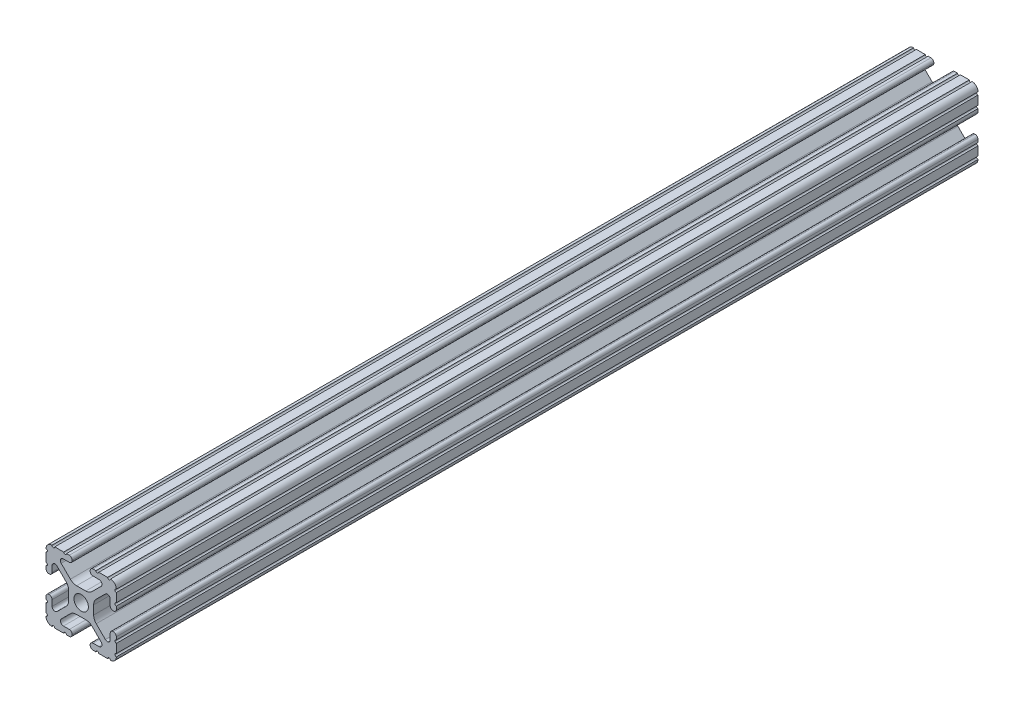
SolidWorks part; units mm, degrees
ref_plane "Front Plane" through (0, 0, 0) normal (0, 0, 1) x (1, 0, 0)
ref_plane "Top Plane" through (0, 0, 0) normal (0, 1, 0) x (1, 0, 0)
ref_plane "Right Plane" through (0, 0, 0) normal (1, 0, 0) x (0, 0, -1)
sketch "Sketch1" plane through (0, 0, 0) normal (0, 0, 1) x (1, 0, 0)
  line L88 (-7.1797, -8.6452) -> (-3.9523, -5.4237)
  line L89 (-1.7093, -4.4958) -> (1.7093, -4.4958)
  line L90 (3.9523, -5.4237) -> (7.1797, -8.6452)
  line L91 (6.4164, -10.4902) -> (4.2875, -10.4902)
  line L92 (3.2385, -11.5392) -> (3.2385, -11.651)
  line L93 (4.2875, -12.7) -> (5.3171, -12.7)
  line L94 (6.3331, -12.7) -> (9.5504, -12.7)
  line L95 (12.7, -9.5504) -> (12.7, -6.3331)
  line L96 (12.7, -5.3171) -> (12.7, -4.2875)
  line L97 (11.651, -3.2385) -> (11.5392, -3.2385)
  line L98 (10.4902, -4.2875) -> (10.4902, -6.4021)
  line L99 (8.7371, -7.1294) -> (5.441, -3.8408)
  line L100 (4.5085, -1.5932) -> (4.5085, 1.5932)
  line L101 (5.441, 3.8408) -> (8.7371, 7.1294)
  line L102 (10.4902, 6.4021) -> (10.4902, 4.2875)
  line L103 (11.5392, 3.2385) -> (11.651, 3.2385)
  line L104 (12.7, 4.2875) -> (12.7, 5.3171)
  line L105 (12.7, 6.3331) -> (12.7, 9.5504)
  line L106 (9.5504, 12.7) -> (6.3331, 12.7)
  line L107 (5.3171, 12.7) -> (4.2875, 12.7)
  line L108 (3.2385, 11.651) -> (3.2385, 11.5392)
  line L109 (4.2875, 10.4902) -> (6.4768, 10.4902)
  line L110 (7.207, 8.7244) -> (3.8983, 5.4232)
  line L111 (1.6558, 4.4958) -> (-1.6558, 4.4958)
  line L112 (-3.8983, 5.4232) -> (-7.207, 8.7244)
  line L113 (-6.4768, 10.4902) -> (-4.2875, 10.4902)
  line L114 (-3.2385, 11.5392) -> (-3.2385, 11.651)
  line L115 (-4.2875, 12.7) -> (-5.3171, 12.7)
  line L116 (-6.3331, 12.7) -> (-9.5504, 12.7)
  line L117 (-12.7, 9.5504) -> (-12.7, 6.3331)
  line L118 (-12.7, 5.3171) -> (-12.7, 4.2875)
  line L119 (-11.651, 3.2385) -> (-11.5392, 3.2385)
  line L120 (-10.4902, 4.2875) -> (-10.4902, 6.4021)
  line L121 (-8.7371, 7.1294) -> (-5.441, 3.8408)
  line L122 (-4.5085, 1.5932) -> (-4.5085, -1.5932)
  line L123 (-5.441, -3.8408) -> (-8.7371, -7.1294)
  line L124 (-10.4902, -6.4021) -> (-10.4902, -4.2875)
  line L125 (-11.5392, -3.2385) -> (-11.651, -3.2385)
  line L126 (-12.7, -4.2875) -> (-12.7, -5.3171)
  line L127 (-12.7, -6.3331) -> (-12.7, -9.5504)
  line L128 (-9.5504, -12.7) -> (-6.3331, -12.7)
  line L129 (-5.3171, -12.7) -> (-4.2875, -12.7)
  line L130 (-3.2385, -11.651) -> (-3.2385, -11.5392)
  line L131 (-4.2875, -10.4902) -> (-6.4164, -10.4902)
  circle A1 centre (0, 0) radius 2.6035
  arc A104 (-7.1797, -8.6452) -> (-6.4164, -10.4902) centre (-6.4164, -9.4098) ccw
  arc A105 (-1.7093, -4.4958) -> (-3.9523, -5.4237) centre (-1.7093, -7.6708) ccw
  arc A106 (3.9523, -5.4237) -> (1.7093, -4.4958) centre (1.7093, -7.6708) ccw
  arc A107 (6.4164, -10.4902) -> (7.1797, -8.6452) centre (6.4164, -9.4098) ccw
  arc A108 (4.2875, -10.4902) -> (3.2385, -11.5392) centre (4.2875, -11.5392) ccw
  arc A109 (3.2385, -11.651) -> (4.2875, -12.7) centre (4.2875, -11.651) ccw
  arc A110 (6.3331, -12.7) -> (5.3171, -12.7) centre (5.8251, -12.7) ccw
  arc A111 (10.5664, -12.6998) -> (9.5504, -12.7) centre (10.0584, -12.7) ccw
  arc A112 (10.5664, -12.6998) -> (12.6998, -10.5664) centre (10.5918, -10.5918) ccw
  arc A113 (12.7, -9.5504) -> (12.6998, -10.5664) centre (12.7, -10.0584) ccw
  arc A114 (12.7, -5.3171) -> (12.7, -6.3331) centre (12.7, -5.8251) ccw
  arc A115 (12.7, -4.2875) -> (11.651, -3.2385) centre (11.651, -4.2875) ccw
  arc A116 (11.5392, -3.2385) -> (10.4902, -4.2875) centre (11.5392, -4.2875) ccw
  arc A117 (8.7371, -7.1294) -> (10.4902, -6.4021) centre (9.4628, -6.4021) ccw
  arc A118 (4.5085, -1.5932) -> (5.441, -3.8408) centre (7.6835, -1.5932) ccw
  arc A119 (5.441, 3.8408) -> (4.5085, 1.5932) centre (7.6835, 1.5932) ccw
  arc A120 (10.4902, 6.4021) -> (8.7371, 7.1294) centre (9.4628, 6.4021) ccw
  arc A121 (10.4902, 4.2875) -> (11.5392, 3.2385) centre (11.5392, 4.2875) ccw
  arc A122 (11.651, 3.2385) -> (12.7, 4.2875) centre (11.651, 4.2875) ccw
  arc A123 (12.7, 6.3331) -> (12.7, 5.3171) centre (12.7, 5.8251) ccw
  arc A124 (12.6998, 10.5664) -> (12.7, 9.5504) centre (12.7, 10.0584) ccw
  arc A125 (12.6998, 10.5664) -> (10.5664, 12.6998) centre (10.5918, 10.5918) ccw
  arc A126 (9.5504, 12.7) -> (10.5664, 12.6998) centre (10.0584, 12.7) ccw
  arc A127 (5.3171, 12.7) -> (6.3331, 12.7) centre (5.8251, 12.7) ccw
  arc A128 (4.2875, 12.7) -> (3.2385, 11.651) centre (4.2875, 11.651) ccw
  arc A129 (3.2385, 11.5392) -> (4.2875, 10.4902) centre (4.2875, 11.5392) ccw
  arc A130 (7.207, 8.7244) -> (6.4768, 10.4902) centre (6.4768, 9.4563) ccw
  arc A131 (1.6558, 4.4958) -> (3.8983, 5.4232) centre (1.6558, 7.6708) ccw
  arc A132 (-3.8983, 5.4232) -> (-1.6558, 4.4958) centre (-1.6558, 7.6708) ccw
  arc A133 (-6.4768, 10.4902) -> (-7.207, 8.7244) centre (-6.4768, 9.4563) ccw
  arc A134 (-4.2875, 10.4902) -> (-3.2385, 11.5392) centre (-4.2875, 11.5392) ccw
  arc A135 (-3.2385, 11.651) -> (-4.2875, 12.7) centre (-4.2875, 11.651) ccw
  arc A136 (-6.3331, 12.7) -> (-5.3171, 12.7) centre (-5.8251, 12.7) ccw
  arc A137 (-10.5664, 12.6998) -> (-9.5504, 12.7) centre (-10.0584, 12.7) ccw
  arc A138 (-10.5664, 12.6998) -> (-12.6998, 10.5664) centre (-10.5918, 10.5918) ccw
  arc A139 (-12.7, 9.5504) -> (-12.6998, 10.5664) centre (-12.7, 10.0584) ccw
  arc A140 (-12.7, 5.3171) -> (-12.7, 6.3331) centre (-12.7, 5.8251) ccw
  arc A141 (-12.7, 4.2875) -> (-11.651, 3.2385) centre (-11.651, 4.2875) ccw
  arc A142 (-11.5392, 3.2385) -> (-10.4902, 4.2875) centre (-11.5392, 4.2875) ccw
  arc A143 (-8.7371, 7.1294) -> (-10.4902, 6.4021) centre (-9.4628, 6.4021) ccw
  arc A144 (-4.5085, 1.5932) -> (-5.441, 3.8408) centre (-7.6835, 1.5932) ccw
  arc A145 (-5.441, -3.8408) -> (-4.5085, -1.5932) centre (-7.6835, -1.5932) ccw
  arc A146 (-10.4902, -6.4021) -> (-8.7371, -7.1294) centre (-9.4628, -6.4021) ccw
  arc A147 (-10.4902, -4.2875) -> (-11.5392, -3.2385) centre (-11.5392, -4.2875) ccw
  arc A148 (-11.651, -3.2385) -> (-12.7, -4.2875) centre (-11.651, -4.2875) ccw
  arc A149 (-12.7, -6.3331) -> (-12.7, -5.3171) centre (-12.7, -5.8251) ccw
  arc A150 (-12.6998, -10.5664) -> (-12.7, -9.5504) centre (-12.7, -10.0584) ccw
  arc A151 (-12.6998, -10.5664) -> (-10.5664, -12.6998) centre (-10.5918, -10.5918) ccw
  arc A152 (-9.5504, -12.7) -> (-10.5664, -12.6998) centre (-10.0584, -12.7) ccw
  arc A153 (-5.3171, -12.7) -> (-6.3331, -12.7) centre (-5.8251, -12.7) ccw
  arc A154 (-4.2875, -12.7) -> (-3.2385, -11.651) centre (-4.2875, -11.651) ccw
  arc A155 (-3.2385, -11.5392) -> (-4.2875, -10.4902) centre (-4.2875, -11.5392) ccw
extrude "Boss-Extrude1" add sketch "Sketch1" along normal mid plane 311.15
